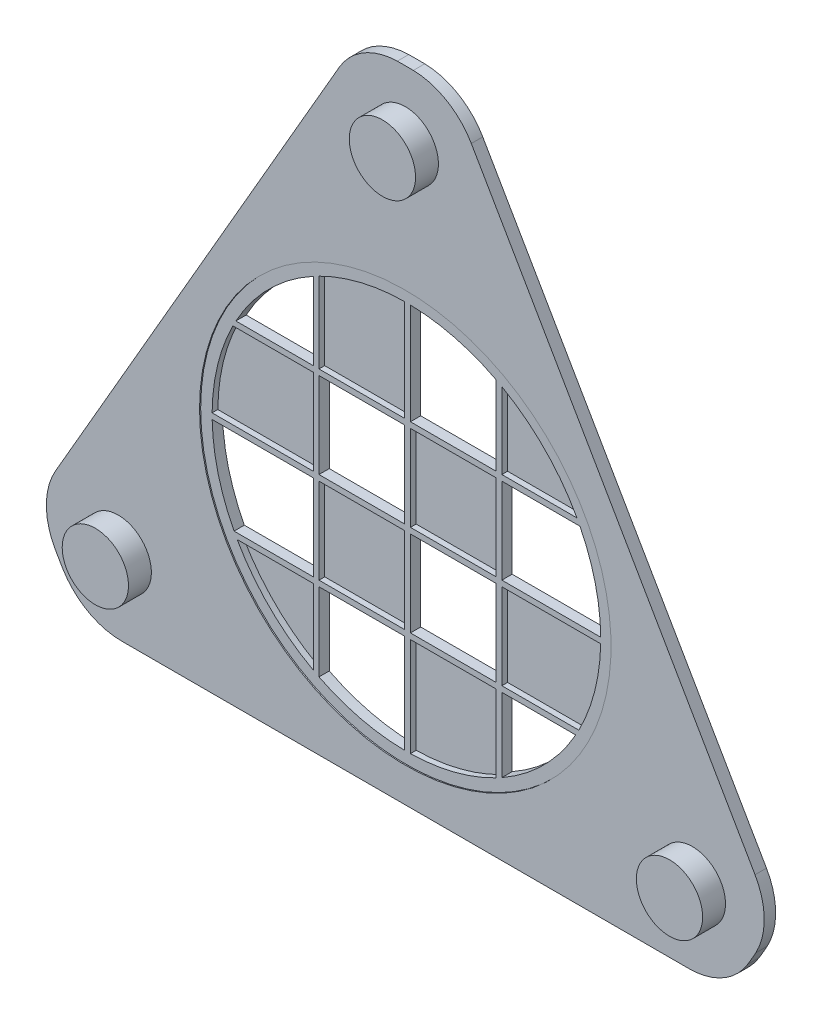
SolidWorks part; units mm, degrees
ref_plane "Спереди" through (0, 0, 0) normal (0, 0, 1) x (1, 0, 0)
ref_plane "Сверху" through (0, 0, 0) normal (0, 1, 0) x (1, 0, 0)
ref_plane "Справа" through (0, 0, 0) normal (1, 0, 0) x (0, 0, -1)
sketch "Sketch1" plane through (0, 0, 0) normal (0, 0, 1) x (1, 0, 0)
  line L0 (3.9, 6.755) -> (7.8, 0) construction
  line L2 (5.85, 10.1325) -> (11.7, 0) construction
  line L4 (7.8, 13.51) -> (15.6, 0) construction
  circle A61 centre (0, 0) radius 20
  circle A131 centre (0, 0) radius 1.25
  circle A484 centre (3.9, 0) radius 1.25
  circle A485 centre (7.8, 0) radius 1.25
  circle A486 centre (11.7, 0) radius 1.25
  circle A487 centre (15.6, 0) radius 1.25
  circle A488 centre (1.95, -3.3775) radius 1.25
  circle A489 centre (3.9, -6.755) radius 1.25
  circle A490 centre (5.85, -10.1325) radius 1.25
  circle A491 centre (7.8, -13.51) radius 1.25
  circle A492 centre (-1.95, -3.3775) radius 1.25
  circle A493 centre (-3.9, -6.755) radius 1.25
  circle A494 centre (-5.85, -10.1325) radius 1.25
  circle A495 centre (-7.8, -13.51) radius 1.25
  circle A496 centre (-3.9, 0) radius 1.25
  circle A497 centre (-7.8, 0) radius 1.25
  circle A498 centre (-11.7, 0) radius 1.25
  circle A499 centre (-15.6, 0) radius 1.25
  circle A500 centre (-1.95, 3.3775) radius 1.25
  circle A501 centre (-3.9, 6.755) radius 1.25
  circle A502 centre (-5.85, 10.1325) radius 1.25
  circle A503 centre (-7.8, 13.51) radius 1.25
  circle A504 centre (1.95, 3.3775) radius 1.25
  circle A505 centre (3.9, 6.755) radius 1.25
  circle A506 centre (5.85, 10.1325) radius 1.25
  circle A507 centre (7.8, 13.51) radius 1.25
  circle A508 centre (5.85, 3.3775) radius 1.25
  circle A509 centre (7.8, 6.755) radius 1.25
  circle A510 centre (9.75, 3.3775) radius 1.25
  circle A511 centre (11.7, 6.755) radius 1.25
  circle A512 centre (9.7491, 10.1341) radius 1.25
  circle A513 centre (13.6509, 3.3759) radius 1.25
  circle A514 centre (5.85, -3.3791) radius 1.25
  circle A515 centre (9.75, -3.3791) radius 1.25
  circle A516 centre (7.8, -6.7566) radius 1.25
  circle A517 centre (11.7, -6.7566) radius 1.25
  circle A518 centre (9.7491, -10.1356) radius 1.25
  circle A519 centre (13.6509, -3.3775) radius 1.25
  circle A520 centre (-0.0013, -6.7573) radius 1.25
  circle A521 centre (1.9487, -10.1348) radius 1.25
  circle A522 centre (-1.9513, -10.1348) radius 1.25
  circle A523 centre (-0.0013, -13.5123) radius 1.25
  circle A524 centre (-3.9032, -13.5123) radius 1.25
  circle A525 centre (3.9005, -13.5123) radius 1.25
  circle A526 centre (-5.8527, -3.3791) radius 1.25
  circle A527 centre (-7.8027, -6.7566) radius 1.25
  circle A528 centre (-9.7527, -3.3791) radius 1.25
  circle A529 centre (-11.7027, -6.7566) radius 1.25
  circle A530 centre (-13.6536, -3.3775) radius 1.25
  circle A531 centre (-9.7518, -10.1356) radius 1.25
  circle A532 centre (-5.8527, 3.3775) radius 1.25
  circle A533 centre (-9.7527, 3.3775) radius 1.25
  circle A534 centre (-7.8027, 6.755) radius 1.25
  circle A535 centre (-11.7027, 6.755) radius 1.25
  circle A536 centre (-9.7518, 10.1341) radius 1.25
  circle A537 centre (-13.6536, 3.3759) radius 1.25
  circle A538 centre (-0.0014, 6.7558) radius 1.25
  circle A539 centre (-1.9514, 10.1333) radius 1.25
  circle A540 centre (1.9486, 10.1333) radius 1.25
  circle A541 centre (-0.0014, 13.5108) radius 1.25
  circle A542 centre (3.9005, 13.5108) radius 1.25
  circle A543 centre (-3.9032, 13.5108) radius 1.25
  circle A544 centre (13.65, -1.1258) radius 2.2517 construction
  circle A545 centre (11.7009, -4.5044) radius 2.2522 construction
  circle A546 centre (9.75, -7.8834) radius 2.2522 construction
  circle A547 centre (7.7987, -11.2591) radius 2.2509 construction
  circle A548 centre (13.65, -1.1258) radius 0.65
  circle A549 centre (11.7009, -4.5044) radius 0.65
  circle A550 centre (9.75, -7.8834) radius 0.65
  circle A551 centre (7.7987, -11.2591) radius 0.65
  circle A552 centre (9.75, -1.1258) radius 0.65
  circle A553 centre (7.8009, -4.5044) radius 0.65
  circle A554 centre (5.85, -7.8834) radius 0.65
  circle A555 centre (3.8987, -11.2591) radius 0.65
  circle A556 centre (5.85, -1.1258) radius 0.65
  circle A557 centre (3.9009, -4.5044) radius 0.65
  circle A558 centre (1.95, -7.8834) radius 0.65
  circle A559 centre (-0.0013, -11.2591) radius 0.65
  circle A560 centre (1.95, -1.1258) radius 0.65
  circle A561 centre (0.0009, -4.5044) radius 0.65
  circle A562 centre (-1.95, -7.8834) radius 0.65
  circle A563 centre (-3.9013, -11.2591) radius 0.65
  circle A564 centre (-1.95, -1.1258) radius 0.65
  circle A565 centre (-3.8991, -4.5044) radius 0.65
  circle A566 centre (-5.85, -7.8834) radius 0.65
  circle A567 centre (-7.8013, -11.2591) radius 0.65
  circle A568 centre (-5.85, -1.1258) radius 0.65
  circle A569 centre (-7.7991, -4.5044) radius 0.65
  circle A570 centre (-9.75, -7.8834) radius 0.65
  circle A572 centre (-9.75, -1.1258) radius 0.65
  circle A573 centre (-11.6991, -4.5044) radius 0.65
  circle A576 centre (-13.65, -1.1258) radius 0.65
  circle A587 centre (0, 2.2517) radius 2.2517 construction
  circle A588 centre (0, 2.2517) radius 0.65
  circle A589 centre (3.9, 2.2517) radius 0.65
  circle A590 centre (7.8, 2.2517) radius 0.65
  circle A591 centre (11.7, 2.2517) radius 0.65
  circle A592 centre (15.6, 2.2517) radius 0.65
  circle A593 centre (1.9491, 5.6297) radius 2.2522 construction
  circle A594 centre (1.9491, 5.6297) radius 0.65
  circle A595 centre (5.8491, 5.6297) radius 0.65
  circle A596 centre (9.7491, 5.6297) radius 0.65
  circle A597 centre (13.6491, 5.6297) radius 0.65
  circle A598 centre (3.8991, 9.0072) radius 2.2522 construction
  circle A599 centre (3.8991, 9.0072) radius 0.65
  circle A600 centre (7.7991, 9.0072) radius 0.65
  circle A601 centre (11.6991, 9.0072) radius 0.65
  circle A602 centre (5.85, 12.3842) radius 2.2517 construction
  circle A603 centre (5.85, 12.3842) radius 0.65
  circle A604 centre (9.75, 12.3842) radius 0.65
  circle A605 centre (5.85, -14.6358) radius 0.65
  circle A606 centre (1.9509, -14.6353) radius 0.65
  circle A607 centre (-1.9491, -14.6353) radius 0.65
  circle A608 centre (-5.85, -14.6358) radius 0.65
  circle A609 centre (-15.6, 2.2517) radius 0.65
  circle A610 centre (-13.65, 5.6281) radius 0.65
  circle A611 centre (-11.7, 9.0056) radius 0.65
  circle A612 centre (-9.75, 12.3842) radius 0.65
  circle A613 centre (-5.85, 12.3842) radius 0.65
  circle A614 centre (-1.95, 12.3842) radius 0.65
  circle A615 centre (1.95, 12.3842) radius 0.65
  circle A616 centre (-7.8, 9.0056) radius 0.65
  circle A617 centre (-9.75, 5.6281) radius 0.65
  circle A618 centre (-11.7, 2.2517) radius 0.65
  circle A619 centre (-3.9, 9.0056) radius 0.65
  circle A620 centre (-5.85, 5.6281) radius 0.65
  circle A621 centre (-7.8, 2.2517) radius 0.65
  circle A622 centre (0, 9.0056) radius 0.65
  circle A623 centre (-1.95, 5.6281) radius 0.65
  circle A624 centre (-3.9, 2.2517) radius 0.65
  circle A625 centre (-15.5991, -4.5044) radius 0.65
  circle A626 centre (-13.65, -7.8834) radius 0.65
  circle A627 centre (-17.55, -7.8834) radius 0.65
  circle A628 centre (-19.5013, -11.2591) radius 0.65
  circle A629 centre (-15.6013, -11.2591) radius 0.65
  circle A630 centre (-11.7013, -11.2591) radius 0.65
  point P51 (0, 0)
  point P125 (-0.0013, -0.0008)
  point P231 (0, 0)
  dimension "D1" = 5
  dimension "D3" = 6
  dimension "D5" = 8
  dimension "D7" = 4
  dimension "D11" = 4
  dimension "D2" = 6
  dimension "D6" = 5
  dimension "D8" = 3
  dimension "D9" = 2
  dimension "D4" = 1.3
  dimension "D10" = 3
ref_plane "Plane1" through (0, 0, 10) normal (0, 0, 1) x (1, 0, 0)
sketch "Sketch2" plane through (0, 0, 10) normal (0, 0, 1) x (1, 0, 0)
  line L0 (-7.65, -15.1815) -> (-7.65, -8.35)
  line L2 (0.35, -16.9964) -> (0.35, -8.35)
  line L4 (-0.15, -16.9993) -> (-0.15, -8.35)
  line L5 (0.1469, -16.9994) -> (0.0704, -8.15) construction
  line L8 (-8.15, -14.919) -> (-8.15, -8.35)
  line L15 (16.9993, 0.15) -> (8.35, 0.15)
  line L17 (16.9964, -0.35) -> (8.35, -0.35)
  line L22 (14.919, 8.15) -> (8.35, 8.15)
  line L24 (15.1815, 7.65) -> (8.35, 7.65)
  line L26 (15.079, -7.85) -> (8.35, -7.85)
  line L28 (14.808, -8.35) -> (8.35, -8.35)
  line L33 (7.85, -15.079) -> (7.85, -8.35)
  line L34 (8.35, -14.808) -> (8.35, -8.35)
  line L36 (7.85, -7.85) -> (7.85, -0.35)
  line L37 (8.35, -7.85) -> (8.35, -0.35)
  line L38 (7.85, -8.35) -> (0.35, -8.35)
  line L39 (7.85, -7.85) -> (0.35, -7.85)
  line L40 (-0.15, -8.35) -> (-7.65, -8.35)
  line L41 (-0.15, -7.85) -> (-7.65, -7.85)
  line L42 (-0.15, -7.85) -> (-0.15, -0.35)
  line L43 (-0.0704, -8.15) -> (-0.1469, -16.9994) construction
  line L44 (0.0678, -7.85) -> (0, 0) construction
  line L45 (0.35, -7.85) -> (0.35, -0.35)
  line L46 (-8.15, -7.85) -> (-15.079, -7.85)
  line L47 (-8.15, -7.85) -> (-8.15, -0.35)
  line L48 (-7.65, -7.85) -> (-7.65, -0.35)
  line L49 (-8.15, -8.35) -> (-14.808, -8.35)
  line L50 (0.003, -0.35) -> (-0.0013, -0.35)
  line L53 (0.0013, 0.15) -> (-0.0013, 0.15)
  line L54 (-0.15, 0.15) -> (-7.65, 0.15)
  line L55 (-0.15, -0.35) -> (-7.65, -0.35)
  line L56 (7.85, -0.35) -> (0.35, -0.35)
  line L59 (7.85, 0.15) -> (0.35, 0.15)
  line L60 (7.85, 0.15) -> (7.85, 7.65)
  line L61 (8.35, 0.15) -> (8.35, 7.65)
  line L62 (-8.15, -0.35) -> (-16.9964, -0.35)
  line L65 (-8.15, 0.15) -> (-16.9993, 0.15)
  line L66 (-8.15, 0.15) -> (-8.15, 7.65)
  line L67 (-7.65, 0.15) -> (-7.65, 7.65)
  line L68 (-0.15, 0.15) -> (-0.15, 7.65)
  line L70 (0, 0) -> (-0.0678, -7.85) construction
  line L71 (0.35, 0.15) -> (0.35, 7.65)
  line L72 (7.85, 8.15) -> (7.85, 15.079)
  line L73 (8.35, 8.15) -> (8.35, 14.808)
  line L74 (7.85, 7.65) -> (0.35, 7.65)
  line L75 (7.85, 8.15) -> (0.35, 8.15)
  line L76 (-0.15, 8.15) -> (-0.15, 16.9993)
  line L79 (0.35, 8.15) -> (0.35, 16.9964)
  line L80 (-0.15, 7.65) -> (-7.65, 7.65)
  line L81 (-0.15, 8.15) -> (-7.65, 8.15)
  line L82 (-8.15, 8.15) -> (-8.15, 14.919)
  line L83 (-7.65, 8.15) -> (-7.65, 15.1815)
  line L84 (-8.15, 7.65) -> (-15.1815, 7.65)
  line L85 (-8.15, 8.15) -> (-14.919, 8.15)
  circle A52 centre (0, 0) radius 17
  circle A53 centre (0, 0) radius 18
  dimension "D1" = 36
  dimension "D4" = 2
  dimension "D2" = 2
  dimension "D5" = 2
  dimension "D6" = 8
  dimension "D7" = 0.5
  dimension "D8" = 8
  dimension "D9" = 8
  dimension "D3" = 8
  dimension "D10" = 0.5
  dimension "D11" = 0.5
extrude "Boss-Extrude1" add sketch "Sketch2" against normal blind 0.9
sketch "Sketch18" plane through (0, 0, 9.1) normal (0, 0, 1) x (1, 0, 0)
  line L0 (-7.85, -15.079) -> (-7.85, -8.15)
  line L2 (0.15, -16.9993) -> (0.15, -8.15)
  line L4 (-0.15, -16.9993) -> (-0.15, -8.15)
  line L5 (0.1469, -16.9994) -> (0.0704, -8.15) construction
  line L8 (-8.15, -14.919) -> (-8.15, -8.15)
  line L15 (16.9993, 0.15) -> (8.15, 0.15)
  line L17 (16.9993, -0.15) -> (8.15, -0.15)
  line L22 (14.919, 8.15) -> (8.15, 8.15)
  line L24 (15.079, 7.85) -> (8.15, 7.85)
  line L26 (15.079, -7.85) -> (8.15, -7.85)
  line L28 (14.919, -8.15) -> (8.15, -8.15)
  line L33 (7.85, -15.079) -> (7.85, -8.15)
  line L34 (8.15, -14.919) -> (8.15, -8.15)
  line L36 (7.85, -7.85) -> (7.85, -0.15)
  line L37 (8.15, -7.85) -> (8.15, -0.15)
  line L38 (7.85, -8.15) -> (0.15, -8.15)
  line L39 (7.85, -7.85) -> (0.15, -7.85)
  line L40 (-0.15, -8.15) -> (-7.85, -8.15)
  line L41 (-0.15, -7.85) -> (-7.85, -7.85)
  line L42 (-0.15, -7.85) -> (-0.15, -0.15)
  line L43 (-0.0704, -8.15) -> (-0.1469, -16.9994) construction
  line L44 (0.0678, -7.85) -> (0, 0) construction
  line L45 (0.15, -7.85) -> (0.15, -0.15)
  line L46 (-8.15, -7.85) -> (-15.079, -7.85)
  line L47 (-8.15, -7.85) -> (-8.15, -0.15)
  line L48 (-7.85, -7.85) -> (-7.85, -0.15)
  line L49 (-8.15, -8.15) -> (-14.919, -8.15)
  line L50 (0.0013, -0.15) -> (-0.0013, -0.15)
  line L53 (0.0013, 0.15) -> (-0.0013, 0.15)
  line L54 (-0.15, 0.15) -> (-7.85, 0.15)
  line L55 (-0.15, -0.15) -> (-7.85, -0.15)
  line L56 (7.85, -0.15) -> (0.15, -0.15)
  line L59 (7.85, 0.15) -> (0.15, 0.15)
  line L60 (7.85, 0.15) -> (7.85, 7.85)
  line L61 (8.15, 0.15) -> (8.15, 7.85)
  line L62 (-8.15, -0.15) -> (-16.9993, -0.15)
  line L65 (-8.15, 0.15) -> (-16.9993, 0.15)
  line L66 (-8.15, 0.15) -> (-8.15, 7.85)
  line L67 (-7.85, 0.15) -> (-7.85, 7.85)
  line L68 (-0.15, 0.15) -> (-0.15, 7.85)
  line L70 (0, 0) -> (-0.0678, -7.85) construction
  line L71 (0.15, 0.15) -> (0.15, 7.85)
  line L72 (7.85, 8.15) -> (7.85, 15.079)
  line L73 (8.15, 8.15) -> (8.15, 14.919)
  line L74 (7.85, 7.85) -> (0.15, 7.85)
  line L75 (7.85, 8.15) -> (0.15, 8.15)
  line L76 (-0.15, 8.15) -> (-0.15, 16.9993)
  line L79 (0.15, 8.15) -> (0.15, 16.9993)
  line L80 (-0.15, 7.85) -> (-7.85, 7.85)
  line L81 (-0.15, 8.15) -> (-7.85, 8.15)
  line L82 (-8.15, 8.15) -> (-8.15, 14.919)
  line L83 (-7.85, 8.15) -> (-7.85, 15.079)
  line L84 (-8.15, 7.85) -> (-15.079, 7.85)
  line L85 (-8.15, 8.15) -> (-14.919, 8.15)
  circle A52 centre (0, 0) radius 17
  circle A53 centre (0, 0) radius 18
  dimension "D1" = 36
  dimension "D4" = 2
  dimension "D2" = 2
  dimension "D5" = 2
  dimension "D6" = 8
  dimension "D8" = 8
  dimension "D9" = 8
  dimension "D3" = 8
extrude "Boss-Extrude10" add sketch "Sketch18" along normal blind 0.4 contours A52 L76 L81 L83 | L74 L60 L59 L71 | L55 L42 L41 L48 | A52 L22 L73 | A52 L84 L66 L65 | A52 L2 L38 L33 | A52 L49 L8 | A52 L26 L37 L17
sketch "Sketch3" plane through (0, 0, 9.1) normal (0, 0, -1) x (-1, 0, 0)
  circle A0 centre (0, 0) radius 17.6
  circle A1 centre (0, 0) radius 35
  circle M33 centre (0, 0) radius 18
extrude "Boss-Extrude2" add sketch "Sketch3" against normal blind 1 contours A1 M33
sketch "Sketch4" plane through (0, 0, 9.1) normal (0, 0, -1) x (-1, 0, 0)
  circle A0 centre (0, 0) radius 29 construction
  circle A1 centre (0, 29) radius 2.9
  circle A2 centre (25.1147, -14.5) radius 2.9
  circle A3 centre (-25.1147, -14.5) radius 2.9
  point P11 (0, 0)
  dimension "D1" = 3
extrude "Boss-Extrude3" add sketch "Sketch4" against normal blind 3
sketch "Sketch7" plane through (0, 0, 9.1) normal (0, 0, -1) x (-1, 0, 0)
  line L1 (0, 42) -> (-36.3731, -21)
  line L2 (-36.3731, -21) -> (36.3731, -21)
  line L3 (36.3731, -21) -> (0, 42)
  circle A2 centre (0, 0) radius 21 construction
  circle A3 centre (0, 0) radius 59.1314
extrude "Cut-Extrude1" cut sketch "Sketch7" against normal through all both and the other way through all
fillet "Fillet1" radius 6 6 edges at (-32.1865, -13.7487, 9.6) (-4.1865, 34.7487, 9.6) (28, -21, 9.6) (-28, -21, 9.6) (4.1865, 34.7487, 9.6) (32.1865, -13.7487, 9.6)
